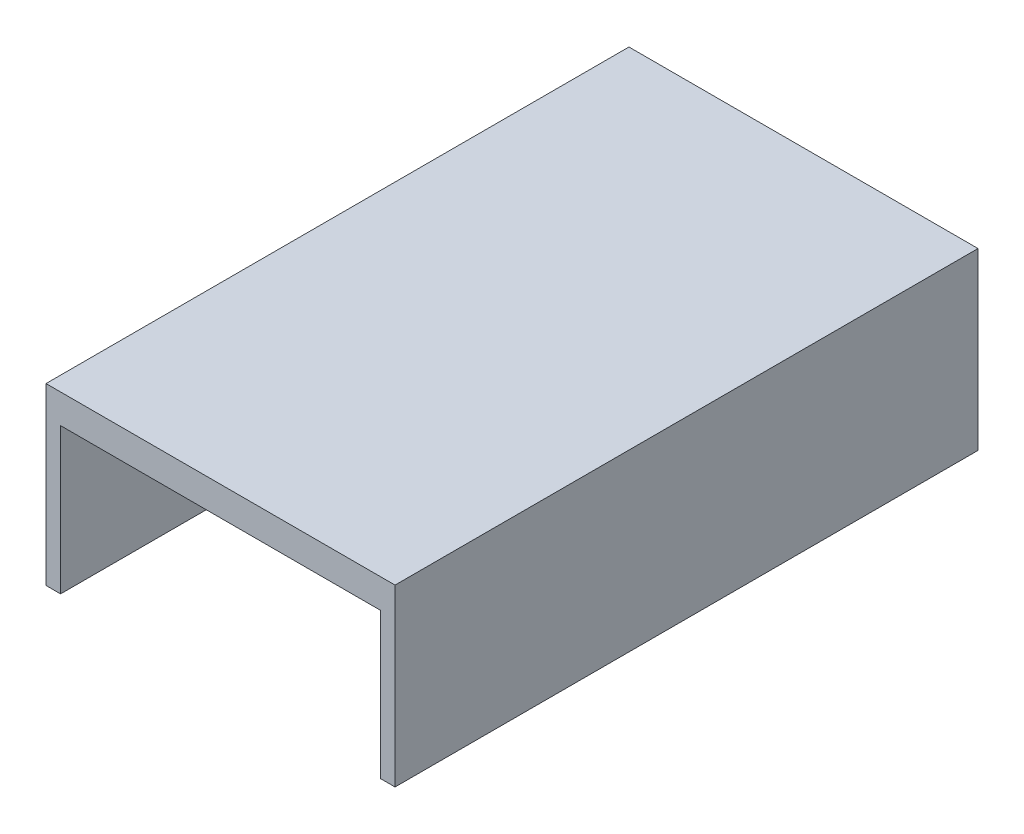
SolidWorks part; units mm, degrees
ref_plane "Alzado" through (0, 0, 0) normal (0, 0, 1) x (1, 0, 0)
ref_plane "Planta" through (0, 0, 0) normal (0, 1, 0) x (1, 0, 0)
ref_plane "Vista lateral" through (0, 0, 0) normal (1, 0, 0) x (0, 0, -1)
sketch "Croquis1" plane through (0, 0, 0) normal (0, 0, 1) x (1, 0, 0)
  line L0 (0, 0) -> (-59.877, 0)
  line L1 (-59.877, 0) -> (-59.877, -60)
  line L2 (-59.877, -60) -> (-54.877, -60)
  line L3 (-54.877, -60) -> (-54.877, -10)
  line L4 (-54.877, -10) -> (54.877, -10)
  line L5 (54.877, -10) -> (54.877, -60)
  line L6 (54.877, -60) -> (59.877, -60)
  line L7 (59.877, -60) -> (59.877, 0)
  line L8 (59.877, 0) -> (0, 0)
  dimension "D1" = 10
  dimension "D2" = 5
  dimension "D3" = 50
extrude "Saliente-Extruir1" add sketch "Croquis1" against normal blind 200
